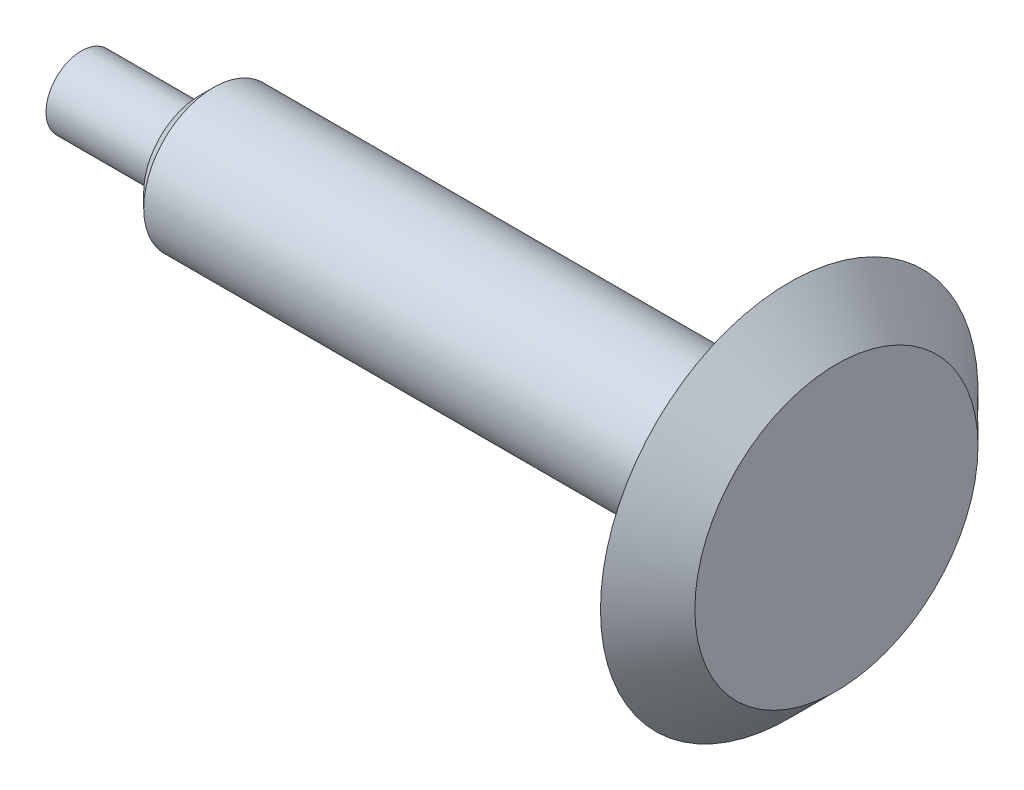
SolidWorks part; units mm, degrees
ref_plane "Plan de face" through (0, 0, 0) normal (0, 0, 1) x (1, 0, 0)
ref_plane "Plan de dessus" through (0, 0, 0) normal (0, 1, 0) x (1, 0, 0)
ref_plane "Plan de droite" through (0, 0, 0) normal (1, 0, 0) x (0, 0, -1)
sketch "Esquisse1" plane through (0, 0, 0) normal (0, 0, 1) x (1, 0, 0)
  line L0 (-576.019, 0) -> (3150.386, 0) construction
  line L1 (-366.4701, 0) -> (-366.4701, -75)
  line L2 (-366.4701, -75) -> (-116.4701, -75)
  line L3 (-116.4701, -75) -> (-116.4701, 0)
  line L4 (-116.4701, 0) -> (-366.4701, 0)
  line L5 (-116.4701, -75) -> (-116.4701, -117.956)
  line L6 (-116.4701, -117.956) -> (-86.4701, -147.956)
  line L7 (-86.4701, -147.956) -> (-86.4701, 0)
  line L8 (-86.4701, 0) -> (-116.4701, 0)
  line L9 (-86.4701, -147.956) -> (1033.5299, -147.956)
  line L10 (1033.5299, -147.956) -> (1033.5299, 0)
  line L11 (1033.5299, 0) -> (-86.4701, 0)
  line L12 (1033.5299, -147.956) -> (1133.5299, -247.956)
  line L13 (1133.5299, -247.956) -> (1133.5299, 0)
  line L14 (1133.5299, 0) -> (1033.5299, 0)
  line L15 (1133.5299, -247.956) -> (1133.5299, -400)
  line L16 (1133.5299, -400) -> (1233.5299, -300)
  line L17 (1233.5299, -300) -> (1233.5299, 0)
  line L18 (1233.5299, 0) -> (1133.5299, 0)
  dimension "D1" = 250
  dimension "D2" = 75
  dimension "D3" = 116.4701
  dimension "D4" = 30
  dimension "D5" = 45
  dimension "D6" = 1600
  dimension "D7" = 1500
  dimension "D8" = 247.956
  dimension "D9" = 400
  dimension "D10" = 100
  dimension "D11" = 45
revolve "Révolution1" add sketch "Esquisse1" angle 360 about L0
